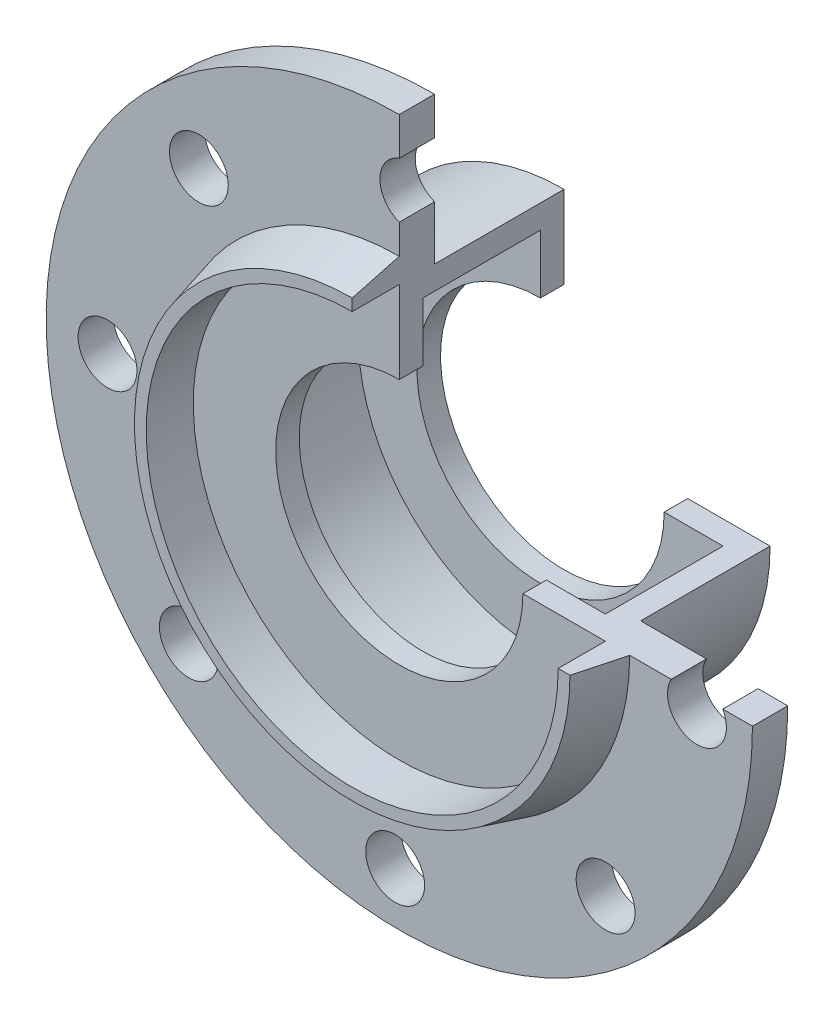
SolidWorks part; units mm, degrees
ref_plane "Front Plane" through (0, 0, 0) normal (0, 0, 1) x (1, 0, 0)
ref_plane "Top Plane" through (0, 0, 0) normal (0, 1, 0) x (1, 0, 0)
ref_plane "Right Plane" through (0, 0, 0) normal (1, 0, 0) x (0, 0, -1)
sketch "Sketch2" plane through (0, 0, 0) normal (1, 0, 0) x (0, 0, -1)
  line L0 (0, 0) -> (-8, 0)
  line L1 (-8, 0) -> (-8, 2)
  line L2 (-8, 2) -> (0, 4.1436)
  line L3 (0, 4.1436) -> (0, 25)
  line L4 (0, 25) -> (6, 25)
  line L5 (6, 25) -> (6, 0)
  line L6 (6, 0) -> (28, 0)
  line L7 (28, 0) -> (28, -14)
  line L8 (28, -14) -> (24, -14)
  line L9 (24, -14) -> (24, -4)
  line L10 (24, -4) -> (4, -4)
  line L11 (4, -4) -> (4, -14)
  line L12 (4, -14) -> (0, -14)
  line L13 (0, -14) -> (0, 0)
  line L14 (-8, 2) -> (21.0316, 2) construction
  line L15 (-8, -35) -> (28, -35) construction
  dimension "D1" = 36
  dimension "D2" = 28
  dimension "D3" = 20
  dimension "D4" = 4
  dimension "D5" = 4
  dimension "D6" = 60
  dimension "D7" = 21
  dimension "D8" = 35
  dimension "D9" = 37
  dimension "D10" = 31
  dimension "D11" = 35
  dimension "D12" = 15
  dimension "D13" = 21
  dimension "D14" = 6
revolve "Revolve1" add sketch "Sketch2" angle 270 about L15
ref_plane "Plane1" through (0, 0, 0) normal (0, 0, 1) x (1, 0, 0)
sketch "Sketch3" plane through (0, 0, 0) normal (0, 0, 1) x (1, 0, 0)
  line L0 (-60, -35) -> (-39.1436, -35) construction
  line L3 (0, 25) -> (0, 4.1436) construction
  circle A0 centre (0, -35) radius 60 construction
  circle A1 centre (0, -35) radius 39.1436 construction
  circle A2 centre (-49.5718, -35) radius 5
  circle A3 centre (-35.7597, -70.7597) radius 5
  circle A4 centre (-0.7071, -86.2789) radius 5
  circle A5 centre (35.0526, -72.4668) radius 5
  circle A6 centre (50.5718, -37.4142) radius 5
  circle A7 centre (36.7597, -1.6546) radius 5
  circle A8 centre (1.7071, 13.8647) radius 5
  circle A9 centre (-34.0526, 0.0526) radius 5
  point P41 (0.5, -36.2071)
  dimension "D1" = 10
  dimension "D2" = 8
extrude "Cut-Extrude1" cut sketch "Sketch3" against normal blind 8 contours A9 | A8 | A7 | A6 | A5 | A4 | A3 | A2
